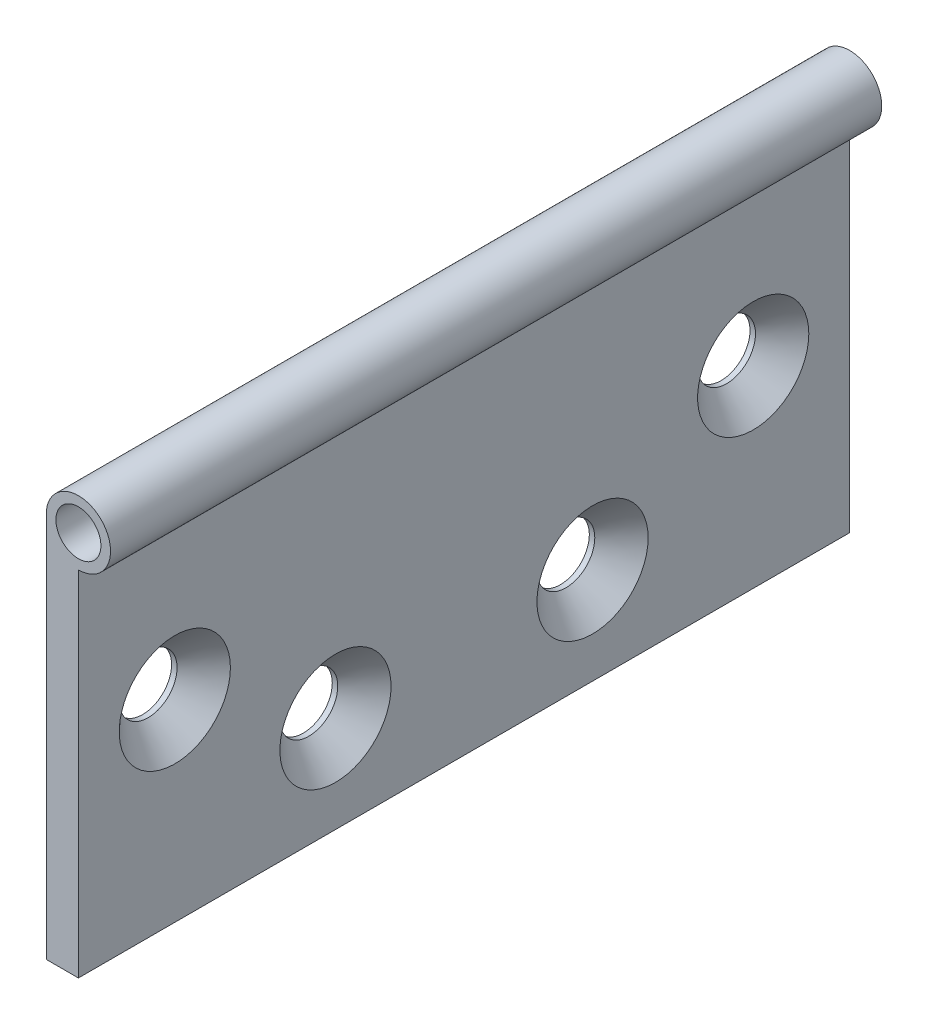
SolidWorks part; units mm, degrees
ref_plane "Front Plane" through (0, 0, 0) normal (0, 0, 1) x (1, 0, 0)
ref_plane "Top Plane" through (0, 0, 0) normal (0, 1, 0) x (1, 0, 0)
ref_plane "Right Plane" through (0, 0, 0) normal (1, 0, 0) x (0, 0, -1)
sketch "Эскиз1" plane through (0, 0, 0) normal (0, 0, 1) x (1, 0, 0)
  line L0 (0, 0) -> (0, 60)
  dimension "D1" = 60
extrude "компоновка для вырезов" add sketch "Эскиз1" along normal mid plane 120 thin
sketch "Эскиз2" plane through (0, 0, 60) normal (0, 0, 1) x (1, 0, 0)
  circle A0 centre (5, 60) radius 5
sweep "По траектории1" add profiles "Эскиз2" path edge at (5, 60, 0)
sketch "Эскиз4" plane through (0, 0, 60) normal (0, 0, 1) x (1, 0, 0)
  circle A0 centre (5, 60) radius 3.5
  arc A1 (5, 55) -> (0, 60) centre (5, 60) ccw construction
extrude "Вырез-Вытянуть1" cut sketch "Эскиз4" against normal through all
hole_wizard "Зенковка для  винта с плоской головкой M81" positions "Эскиз6" profile "Эскиз5" countersink size "M8" standard "Ansi Metric" end condition through all
sketch "Эскиз6" plane through (5, 0, 0) normal (1, 0, 0) x (0, 0, -1)
  point P0 (-45, 30)
  point P2 (-20, 15)
  dimension "D1" = 30
  dimension "D2" = 15
  dimension "D3" = 15
  dimension "D4" = 40
sketch "Эскиз5" plane through (5, 30, 45) normal (0, 1, 0) x (0, 0, -1)
  line L0 (0, 0) -> (0, 5)
  line L1 (0, 5) -> (4.5, 5)
  line L2 (4.5, 5) -> (4.5, 4.15)
  line L3 (4.5, 4.15) -> (8.65, 0)
  line L5 (8.65, 0) -> (0, 0)
  line L6 (-4.5, 4.15) -> (-8.65, 0) construction
  line L11 (0, -6.35) -> (0, 107.95) construction
  dimension "Диаметр сквозного отверстия" = 9
  dimension "Глубина сквозного отверстия" = 5
  dimension "Диаметр передней зенковки" = 17.3
  dimension "Угол передней зенковки" = 90
mirror "Зеркальное отражение1" about plane through (0, 0, 0) normal (0, 0, 1) of "Зенковка для  винта с плоской головкой M81"
sketch "Эскиз8" plane through (5, 0, 0) normal (1, 0, 0) x (0, 0, -1)
  line L0 (-36, 65) -> (-36, 54)
  line L1 (-12, 65) -> (-12, 54)
  line L2 (-60, 65) -> (-60, 55) construction
  line L3 (60, 54) -> (-60, 54)
  line L4 (60, 54) -> (-60, 54)
  line L5 (60, 55) -> (60, 65) construction
  line L6 (-60, 65) -> (-60, 55)
  line L7 (60, 55) -> (60, 65)
  line L8 (-36, 65) -> (-36, 54)
  line L9 (60, 65) -> (-60, 65) construction
  line L10 (0, 80.7408) -> (0, 0) construction
  line L11 (12, 65) -> (12, 54)
  line L12 (36, 65) -> (36, 54)
  dimension "D2" = 24
  dimension "D3" = 24
  dimension "D1" = 1
sketch "Эскиз11" plane through (5, 0, 0) normal (1, 0, 0) x (0, 0, -1)
  line L0 (-60, 65) -> (-60, 55) construction
  line L1 (60, 54) -> (-60, 54) construction
  line L2 (-60, 65) -> (-60, 55)
  line L3 (60, 54) -> (-60, 54)
  line L4 (60, 0) -> (60, 55)
  line L5 (60, 55) -> (-60, 55)
  line L6 (-60, 55) -> (-60, 0)
  line L7 (-60, 0) -> (60, 0)
  line L8 (60, 0) -> (60, 55)
  line L9 (60, 55) -> (-60, 55)
  line L10 (-60, 55) -> (-60, 0)
  line L11 (-60, 0) -> (60, 0)
  line L12 (-60, 65) -> (-60, 60) construction
  dimension "D1" = 0
sketch "Эскиз13" plane through (5, 0, 0) normal (1, 0, 0) x (0, 0, -1)
  line L0 (13, 65) -> (35, 65)
  line L1 (-13, 54) -> (-35, 54)
  line L4 (60, 54) -> (-60, 54) construction
  line L5 (35, 54) -> (13, 54)
  line L6 (-60, 65) -> (-60, 55) construction
  line L7 (-60, 65) -> (-60, 55)
  line L8 (-35, 65) -> (-13, 65)
  line L9 (60, 55) -> (60, 65) construction
  line L10 (60, 55) -> (60, 65)
  line L11 (60, 0) -> (60, 55) construction
  line L12 (60, 0) -> (60, 55)
  line L13 (-60, 55) -> (-60, 0) construction
  line L14 (-60, 55) -> (-60, 0)
  line L17 (-35, 65) -> (-35, 54)
  line L18 (-35, 65) -> (-35, 54)
  line L20 (35, 65) -> (35, 54)
  line L21 (35, 65) -> (35, 54)
  line L23 (13, 65) -> (13, 54)
  line L24 (13, 65) -> (13, 54)
  line L26 (-13, 65) -> (-13, 54)
  line L27 (-13, 65) -> (-13, 54)
  dimension "D1" = 1
  dimension "D2" = 1
  dimension "D3" = 1
  dimension "D4" = 1
equation "\"D1@Эскиз6\"= \"D1@Эскиз1\" / 2"
equation "\"D4@Эскиз6\" = \"D1@компоновка для вырезов\" / 3"
equation "\"D2@Эскиз8\" = \"D1@компоновка для вырезов\" / 5"
equation "\"D3@Эскиз8\"= \"D1@компоновка для вырезов\" / 5"
